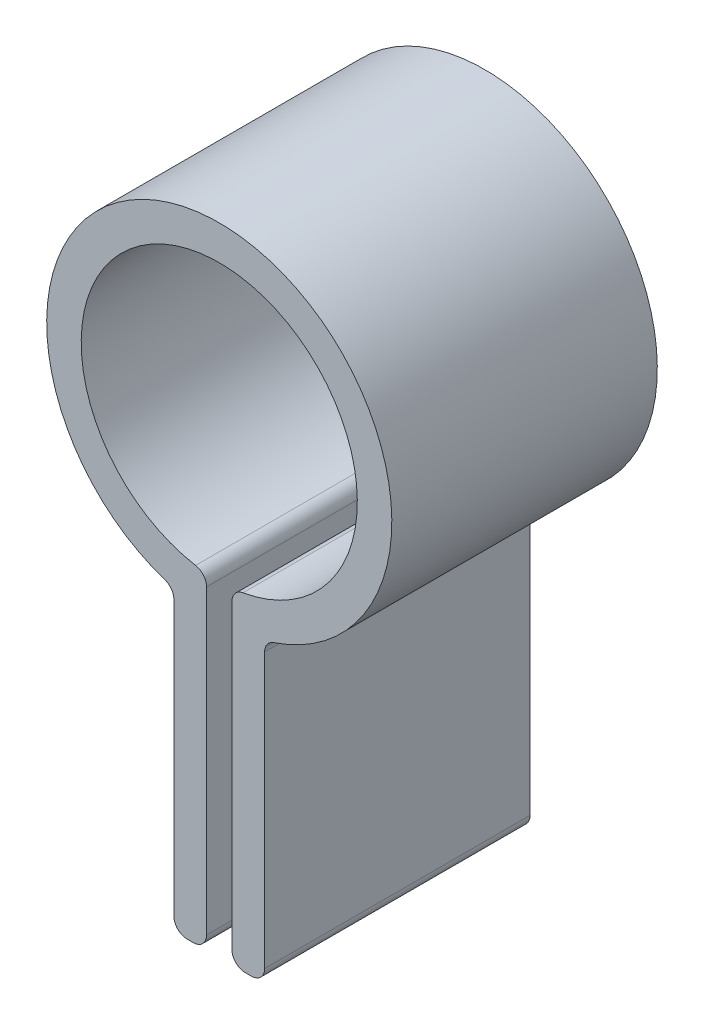
SolidWorks part; units mm, degrees
ref_plane "Front Plane" through (0, 0, 0) normal (0, 0, 1) x (1, 0, 0)
ref_plane "Top Plane" through (0, 0, 0) normal (0, 1, 0) x (1, 0, 0)
ref_plane "Right Plane" through (0, 0, 0) normal (1, 0, 0) x (0, 0, -1)
sketch "Sketch1" plane through (0, 0, 0) normal (0, 0, 1) x (1, 0, 0)
  line L0 (0, 0) -> (0, -18.3156)
  line L1 (0.4787, -5.6154) -> (0.4787, -16.9717)
  line L2 (0.9787, -17.4717) -> (1.2098, -17.4717)
  line L3 (1.7098, -16.9717) -> (1.7098, -6.642)
  line L4 (-0.4787, -5.6154) -> (-0.4787, -16.9717)
  line L5 (-0.9787, -17.4717) -> (-1.2098, -17.4717)
  line L6 (-1.7098, -16.9717) -> (-1.7098, -6.642)
  arc A0 (0.8928, -5.1228) -> (-0.8928, -5.1228) centre (0, 0) ccw
  arc A1 (2.052, -6.1676) -> (-2.052, -6.1676) centre (0, 0) ccw
  arc A2 (-1.2098, -17.4717) -> (-1.7098, -16.9717) centre (-1.2098, -16.9717) cw
  arc A3 (-0.9787, -17.4717) -> (-0.4787, -16.9717) centre (-0.9787, -16.9717) ccw
  arc A4 (0.9787, -17.4717) -> (0.4787, -16.9717) centre (0.9787, -16.9717) cw
  arc A5 (1.2098, -17.4717) -> (1.7098, -16.9717) centre (1.2098, -16.9717) ccw
  arc A6 (-2.052, -6.1676) -> (-1.7098, -6.642) centre (-2.2098, -6.642) cw
  arc A7 (1.7098, -6.642) -> (2.052, -6.1676) centre (2.2098, -6.642) cw
  arc A8 (-0.8928, -5.1228) -> (-0.4787, -5.6154) centre (-0.9787, -5.6154) cw
  arc A9 (0.4787, -5.6154) -> (0.8928, -5.1228) centre (0.9787, -5.6154) cw
  point P12 (-1.7098, -17.4717)
  point P16 (-0.4787, -17.4717)
  point P19 (0.4787, -17.4717)
  point P22 (1.7098, -17.4717)
  dimension "D1" = 0.5
  dimension "D2" = 0.5
extrude "Boss-Extrude1" add sketch "Sketch1" along normal blind 10 contours A1 A6 L6 A2 L5 A3 L4 A8 A0 A9 L1 A4 L2 A5 L3 A7
